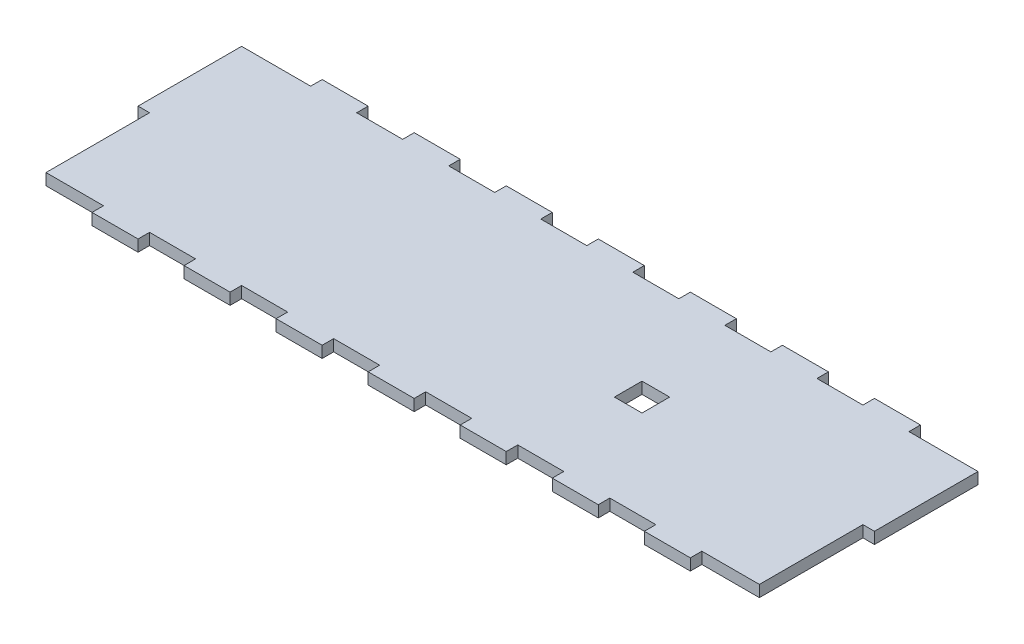
SolidWorks part; units mm, degrees
material "Oak"
ref_plane "Front Plane" through (0, 0, 0) normal (0, 0, 1) x (1, 0, 0)
ref_plane "Top Plane" through (0, 0, 0) normal (0, 1, 0) x (1, 0, 0)
ref_plane "Right Plane" through (0, 0, 0) normal (1, 0, 0) x (0, 0, -1)
sketch "Sketch1" plane through (0, 0, 0) normal (0, 1, 0) x (1, 0, 0)
  line L1 (80, 25) -> (-80, 25)
  line L2 (80, 25) -> (80, -25)
  line L3 (80, -25) -> (-80, -25)
  line L4 (-80, 25) -> (-80, -25)
  line L5 (80, 25) -> (-80, -25) construction
  line L6 (80, -25) -> (-80, 25) construction
  point P0 (0, 0)
  dimension "D1" = 50
  dimension "D2" = 160
extrude "Boss-Extrude1" add sketch "Sketch1" along normal mid plane 2.5
sketch "Sketch2" plane through (0, 1.25, 0) normal (0, 1, 0) x (1, 0, 0)
  line L0 (5, -22.5) -> (-5, -22.5) construction
  line L5 (80, 25) -> (-80, 25) construction
  line L6 (5, 25) -> (-5, 25) construction
  line L11 (5, -22.5) -> (5, -25) construction
  line L24 (5, -25) -> (-5, -25) construction
  line L85 (5, 25) -> (5, 22.5) construction
  line L86 (5, 22.5) -> (-5, 22.5) construction
  line L87 (-5, 25) -> (-5, 22.5) construction
  line L88 (80, -25) -> (80, 25) construction
  line L89 (-5, -22.5) -> (-5, -25) construction
  line L90 (-80, -25) -> (80, -25) construction
  line L115 (25, 22.5) -> (25, 25)
  line L140 (5, 22.5) -> (15, 22.5)
  line L141 (5, 22.5) -> (5, 25)
  line L142 (5, 25) -> (15, 25)
  line L143 (15, 22.5) -> (15, 25)
  line L144 (5, -22.5) -> (15, -22.5)
  line L145 (5, -22.5) -> (5, -25)
  line L146 (5, -25) -> (15, -25)
  line L147 (15, -22.5) -> (15, -25)
  line L148 (25, 22.5) -> (35, 22.5)
  line L149 (35, 22.5) -> (35, 25)
  line L150 (25, 25) -> (35, 25)
  line L151 (25, -22.5) -> (25, -25)
  line L152 (25, -22.5) -> (35, -22.5)
  line L153 (35, -22.5) -> (35, -25)
  line L154 (25, -25) -> (35, -25)
  line L155 (45, 22.5) -> (45, 25)
  line L156 (45, 22.5) -> (55, 22.5)
  line L157 (55, 22.5) -> (55, 25)
  line L158 (45, 25) -> (55, 25)
  line L159 (45, -22.5) -> (45, -25)
  line L160 (45, -22.5) -> (55, -22.5)
  line L161 (55, -22.5) -> (55, -25)
  line L162 (45, -25) -> (55, -25)
  line L163 (5, 22.5) -> (25, 22.5) construction
  line L164 (-15, 22.5) -> (-15, 25)
  line L165 (-15, 22.5) -> (-5, 22.5)
  line L166 (-5, 22.5) -> (-5, 25)
  line L167 (-15, 25) -> (-5, 25)
  line L168 (-15, -22.5) -> (-15, -25)
  line L169 (-15, -22.5) -> (-5, -22.5)
  line L170 (-5, -22.5) -> (-5, -25)
  line L171 (-15, -25) -> (-5, -25)
  line L172 (-35, 22.5) -> (-35, 25)
  line L173 (-35, 22.5) -> (-25, 22.5)
  line L174 (-25, 22.5) -> (-25, 25)
  line L175 (-35, 25) -> (-25, 25)
  line L176 (-35, -22.5) -> (-35, -25)
  line L177 (-35, -22.5) -> (-25, -22.5)
  line L178 (-25, -22.5) -> (-25, -25)
  line L179 (-35, -25) -> (-25, -25)
  line L180 (-55, 22.5) -> (-55, 25)
  line L181 (-55, 22.5) -> (-45, 22.5)
  line L182 (-45, 22.5) -> (-45, 25)
  line L183 (-55, 25) -> (-45, 25)
  line L184 (-55, -22.5) -> (-55, -25)
  line L185 (-55, -22.5) -> (-45, -22.5)
  line L186 (-45, -22.5) -> (-45, -25)
  line L187 (-55, -25) -> (-45, -25)
  line L188 (5, 22.5) -> (-15, 22.5) construction
  line L190 (80, 25) -> (65, 25)
  line L191 (80, 25) -> (80, 22.5)
  line L192 (80, 22.5) -> (65, 22.5)
  line L193 (65, 25) -> (65, 22.5)
  line L194 (80, -25) -> (65, -25)
  line L195 (80, -25) -> (80, -22.5)
  line L196 (80, -22.5) -> (65, -22.5)
  line L197 (65, -25) -> (65, -22.5)
  line L198 (-80, 25) -> (-65, 25)
  line L199 (-80, 25) -> (-80, 22.5)
  line L200 (-80, 22.5) -> (-65, 22.5)
  line L201 (-65, 25) -> (-65, 22.5)
  line L202 (-80, -25) -> (-65, -25)
  line L203 (-80, -25) -> (-80, -22.5)
  line L204 (-80, -22.5) -> (-65, -22.5)
  line L205 (-65, -25) -> (-65, -22.5)
  dimension "D2" = 2.5
  dimension "D1" = 10
  dimension "D3" = 75
  dimension "D4" = 10
  dimension "D5" = 2.5
  dimension "D6" = 75
  dimension "D7" = 10
  dimension "D8" = 10
  dimension "D10" = 20
  dimension "D12" = 20
  dimension "D13" = 2.5
  dimension "D14" = 2.5
  dimension "D15" = 2.5
  dimension "D16" = 2.5
  dimension "D17" = 10
  dimension "D18" = 10
  dimension "D19" = 10
  dimension "D20" = 10
  dimension "D9" = 3
  dimension "D11" = 4
extrude "Cut-Extrude1" cut sketch "Sketch2" against normal blind 4
sketch "Sketch3" plane through (0, 1.25, 0) normal (0, 1, 0) x (1, 0, 0)
  line L0 (0, 0) -> (0, 25) construction
  line L1 (80, 0) -> (77.5, 0)
  line L2 (80, 0) -> (80, -22.5)
  line L3 (80, -22.5) -> (77.5, -22.5)
  line L4 (77.5, 0) -> (77.5, -22.5)
  line L5 (80, -22.5) -> (80, 22.5) construction
  line L6 (5, 25) -> (-5, 25) construction
  line L14 (80, -22.5) -> (65, -22.5) construction
  line L15 (-77.5, 0) -> (-77.5, -22.5)
  line L16 (-80, -22.5) -> (-77.5, -22.5)
  line L17 (-80, 0) -> (-80, -22.5)
  line L18 (-80, 0) -> (-77.5, 0)
  point P5 (78.75, -22.5)
  dimension "D2" = 2.5
  dimension "D3" = 22.5
extrude "Cut-Extrude2" cut sketch "Sketch3" against normal through all
sketch "Sketch4" plane through (0, -1.25, 0) normal (0, -1, 0) x (-1, 0, 0)
  line L1 (-26.5, 3) -> (-32.5, 3)
  line L2 (-26.5, 3) -> (-26.5, -3)
  line L3 (-26.5, -3) -> (-32.5, -3)
  line L4 (-32.5, 3) -> (-32.5, -3)
  line L5 (-80, 0) -> (-80, 22.5) construction
  point P6 (-26.5, 0)
  dimension "D1" = 47.5
  dimension "D2" = 6
extrude "Cut-Extrude3" cut sketch "Sketch4" against normal up to next
equation "\"thick\"= 0.25"
equation "\"D2@Sketch3\"=\"thick\""
equation "\"corner\"=2.1"
equation "\"D3@Sketch3\"=( +\"width\" - \"thick\" * 2 ) / 2"
equation "\"D1@Boss-Extrude1\"=\"thick\""
equation "\"length\"= 16"
equation "\"width\"=5"
equation "\"D1@Sketch1\"=\"width\""
equation "\"D2@Sketch1\"=\"length\""
equation "\"hole_length\"=1"
equation "\"D1@Sketch2\"=\"hole_length\""
equation "\"D6@Sketch2\"=\"D3@Sketch2\""
equation "\"D5@Sketch2\"=\"thick\""
equation "\"D4@Sketch2\"=\"hole_length\""
equation "\"D3@Sketch2\"=(\"length\" - 1) / 2"
equation "\"D2@Sketch2\"=\"thick\""
equation "\"D7@Sketch2\"=\"D1@Sketch2\""
equation "\"D8@Sketch2\"=\"D1@Sketch2\""
equation "\"D13@Sketch2\"=\"thick\""
equation "\"D14@Sketch2\"=\"D13@Sketch2\""
equation "\"D15@Sketch2\"=\"D13@Sketch2\""
equation "\"D16@Sketch2\"=\"D15@Sketch2\""
equation "\"D17@Sketch2\"=\"hole_length\""
equation "\"D18@Sketch2\"=\"D17@Sketch2\""
equation "\"D19@Sketch2\"=\"D18@Sketch2\""
equation "\"D20@Sketch2\"=\"D19@Sketch2\""
